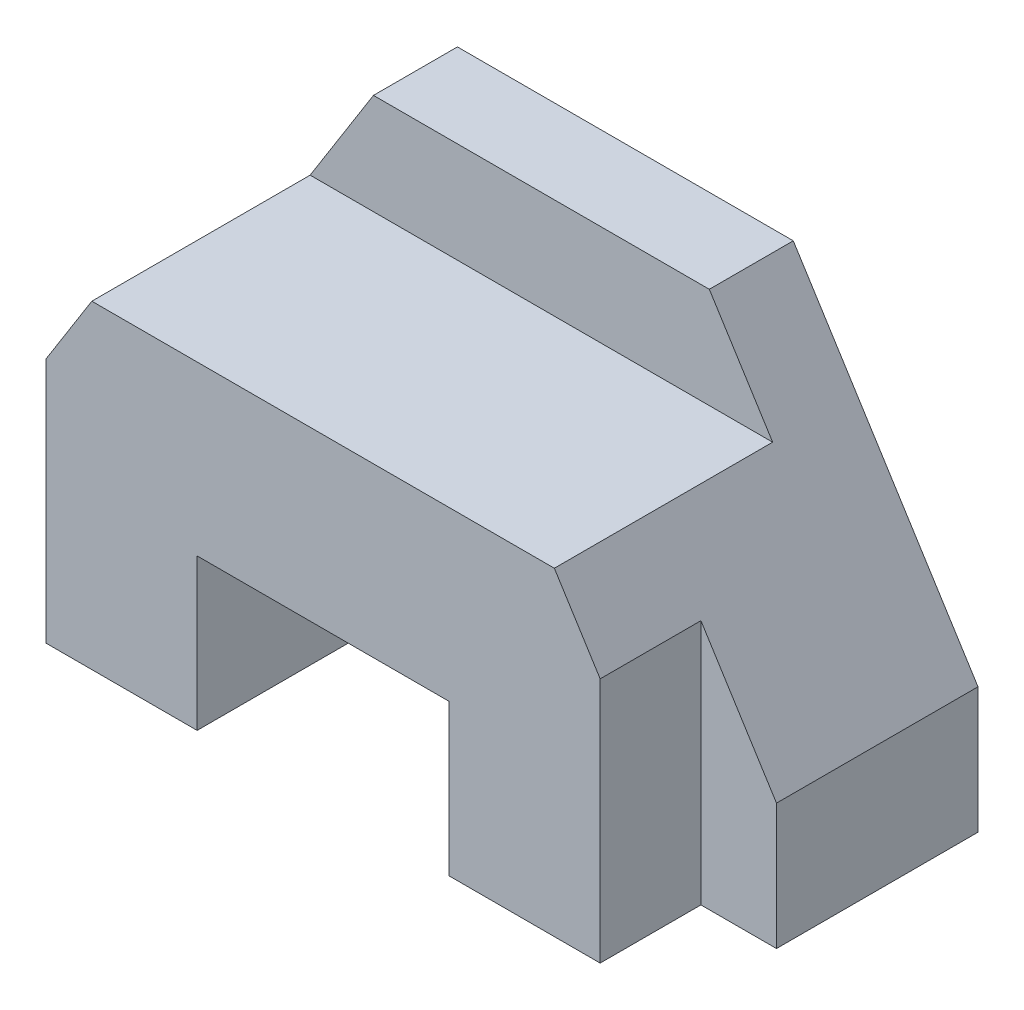
SolidWorks part; units mm, degrees
ref_plane "Alzado" through (0, 0, 0) normal (0, 0, 1) x (1, 0, 0)
ref_plane "Planta" through (0, 0, 0) normal (0, 1, 0) x (1, 0, 0)
ref_plane "Vista lateral" through (0, 0, 0) normal (1, 0, 0) x (0, 0, -1)
sketch "Croquis1" plane through (0, 0, 0) normal (0, 0, 1) x (1, 0, 0)
  line L0 (0, 0) -> (0, 50) construction
  line L1 (42, 0) -> (-42, 0)
  line L2 (-42, 0) -> (-42, 15)
  line L3 (-42, 15) -> (-20, 50)
  line L4 (-20, 50) -> (20, 50)
  line L5 (42, 0) -> (42, 15)
  line L6 (42, 15) -> (20, 50)
  dimension "D1" = 15
  dimension "D2" = 50
  dimension "D3" = 40
  dimension "D4" = 84
extrude "Saliente-Extruir1" add sketch "Croquis1" along normal mid plane 36
sketch "Croquis2" plane through (0, 0, 18) normal (0, 0, 1) x (1, 0, 0)
  line L0 (-27.5429, 38) -> (27.5429, 38)
  line L1 (-20, 50) -> (-42, 15) construction
  line L2 (42, 15) -> (20, 50) construction
  line L3 (-42, 0) -> (42, 0) construction
  line L9 (42, 0) -> (42, 15)
  line L10 (42, 15) -> (20, 50)
  line L11 (20, 50) -> (-20, 50)
  line L12 (-20, 50) -> (-42, 15)
  line L13 (-42, 15) -> (-42, 0)
  line L14 (-42, 0) -> (42, 0)
  line L16 (27.5429, 38) -> (20, 50)
  line L17 (20, 50) -> (-20, 50)
  line L18 (-20, 50) -> (-27.5429, 38)
  dimension "D2" = 38
  dimension "D1" = 0
extrude "Cortar-Extruir1" cut sketch "Croquis2" against normal blind 26
sketch "Croquis3" plane through (0, 0, 18) normal (0, 0, 1) x (1, 0, 0)
  line L0 (-33, 0) -> (-33, 29.3182)
  line L1 (33, 29.3182) -> (33, 0)
  line L2 (33, 0) -> (42, 0)
  line L6 (42, 15) -> (27.5429, 38)
  line L7 (27.5429, 38) -> (-27.5429, 38)
  line L8 (-27.5429, 38) -> (-42, 15)
  line L9 (-42, 15) -> (-42, 0)
  line L10 (-42, 0) -> (42, 0)
  line L11 (42, 0) -> (42, 15)
  line L12 (42, 15) -> (33, 29.3182)
  line L14 (-33, 29.3182) -> (-42, 15)
  line L15 (-42, 15) -> (-42, 0)
  line L16 (-42, 0) -> (-33, 0)
  line L17 (42, 0) -> (42, 15)
  dimension "D2" = 66
  dimension "D1" = 0
extrude "Cortar-Extruir2" cut sketch "Croquis3" against normal blind 12
sketch "Croquis4" plane through (0, 0, 18) normal (0, 0, 1) x (1, 0, 0)
  line L0 (-33, 0) -> (33, 0) construction
  line L1 (-15, 0) -> (15, 0)
  line L2 (-15, 0) -> (-15, 18)
  line L3 (-15, 18) -> (15, 18)
  line L4 (15, 0) -> (15, 18)
  point P6 (0, 18)
  dimension "D1" = 30
  dimension "D2" = 18
extrude "Cortar-Extruir3" cut sketch "Croquis4" against normal through all
